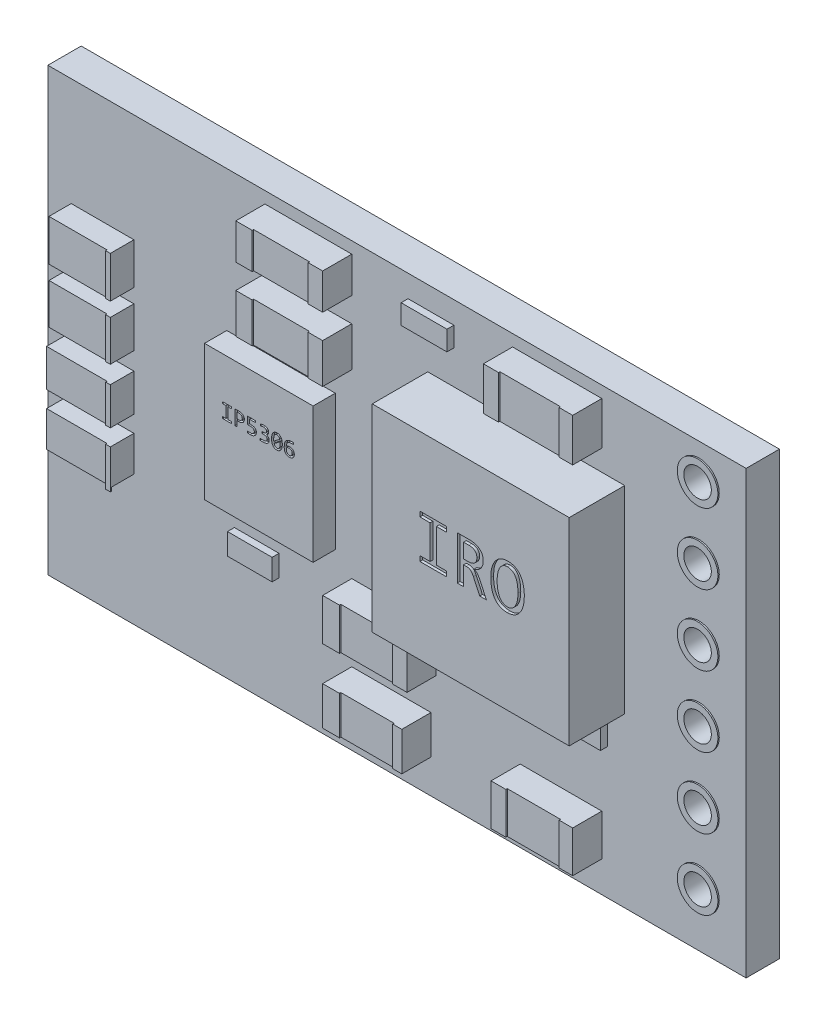
SolidWorks part; units mm, degrees
ref_plane "Plan de face" through (0, 0, 0) normal (0, 0, 1) x (1, 0, 0)
ref_plane "Plan de dessus" through (0, 0, 0) normal (0, 1, 0) x (1, 0, 0)
ref_plane "Plan de droite" through (0, 0, 0) normal (1, 0, 0) x (0, 0, -1)
sketch "Esquisse3" plane through (0, 0, 0) normal (0, 0, 1) x (1, 0, 0)
  line L0 (630.2148, 278.395) -> (630.1921, 275.8551) construction
  line L2 (606.726, 282.2036) -> (631.8802, 282.2036)
  line L3 (606.726, 282.2036) -> (606.726, 266.303)
  line L4 (606.726, 266.303) -> (631.8802, 266.303)
  line L5 (631.8802, 282.2036) -> (631.8802, 266.303)
  dimension "D1" = 2.54
sketch "condo" plane through (0, 0, 0) normal (0, 0, 1) x (1, 0, 0)
  line L1 (620.4109, 279.4811) -> (627.5068, 279.4811)
  line L2 (620.4109, 279.4811) -> (620.4109, 272.3562)
  line L3 (620.4109, 272.3562) -> (627.5068, 272.3562)
  line L4 (627.5068, 279.4811) -> (627.5068, 272.3562)
sketch "resistors" plane through (0, 0, 0) normal (0, 0, 1) x (1, 0, 0)
  line L1 (614.546, 281.7836) -> (617.6739, 281.7836)
  line L2 (614.546, 281.7836) -> (614.546, 280.4948)
  line L3 (614.546, 280.4948) -> (617.6739, 280.4948)
  line L4 (617.6739, 281.7836) -> (617.6739, 280.4948)
  line L5 (614.546, 279.6114) -> (617.6739, 279.6114)
  line L6 (614.546, 279.6114) -> (614.546, 278.1778)
  line L7 (614.546, 278.1778) -> (617.6739, 278.1778)
  line L8 (617.6739, 279.6114) -> (617.6739, 278.1778)
  line L9 (623.4665, 281.7836) -> (626.6814, 281.7836)
  line L10 (623.4665, 281.7836) -> (623.4665, 280.2341)
  line L11 (623.4665, 280.2341) -> (626.6814, 280.2341)
  line L12 (626.6814, 281.7836) -> (626.6814, 280.2341)
  line L13 (617.6739, 271.6611) -> (620.715, 271.6611)
  line L14 (617.6739, 271.6611) -> (617.6739, 270.1551)
  line L15 (617.6739, 270.1551) -> (620.715, 270.1551)
  line L16 (620.715, 271.6611) -> (620.715, 270.1551)
  line L17 (617.6739, 268.9097) -> (620.5268, 268.9097)
  line L18 (617.6739, 268.9097) -> (617.6739, 267.5195)
  line L19 (617.6739, 267.5195) -> (620.5268, 267.5195)
  line L20 (620.5268, 268.9097) -> (620.5268, 267.5195)
  line L21 (623.7416, 268.9097) -> (626.6814, 268.9097)
  line L22 (623.7416, 268.9097) -> (623.7416, 267.4181)
  line L23 (623.7416, 267.4181) -> (626.6814, 267.4181)
  line L24 (626.6814, 268.9097) -> (626.6814, 267.4181)
sketch "ic  et diodes" plane through (0, 0, 0) normal (0, 0, 1) x (1, 0, 0)
  line L1 (613.1702, 277.1496) -> (617.0802, 277.1496)
  line L2 (613.1702, 277.1496) -> (613.1702, 272.2694)
  line L3 (613.1702, 272.2694) -> (617.0802, 272.2694)
  line L4 (617.0802, 277.1496) -> (617.0802, 272.2694)
  line L5 (609.825, 278.3081) -> (607.5659, 278.3081)
  line L6 (609.825, 278.3081) -> (609.825, 276.8165)
  line L7 (609.825, 276.8165) -> (607.5659, 276.8165)
  line L8 (607.5659, 278.3081) -> (607.5659, 276.8165)
  line L9 (609.825, 276.3097) -> (607.5659, 276.3097)
  line L10 (609.825, 276.3097) -> (609.825, 274.847)
  line L11 (609.825, 274.847) -> (607.5659, 274.847)
  line L12 (607.5659, 276.3097) -> (607.5659, 274.847)
  line L13 (609.825, 274.2099) -> (607.479, 274.2099)
  line L14 (609.825, 274.2099) -> (609.825, 272.8631)
  line L15 (609.825, 272.8631) -> (607.479, 272.8631)
  line L16 (607.479, 274.2099) -> (607.479, 272.8631)
  line L17 (609.825, 272.2694) -> (607.479, 272.2694)
  line L18 (609.825, 272.2694) -> (609.825, 270.995)
  line L19 (609.825, 270.995) -> (607.479, 270.995)
  line L20 (607.479, 272.2694) -> (607.479, 270.995)
sketch "resistrors" plane through (0, 0, 0) normal (0, 0, 1) x (1, 0, 0)
  line L1 (619.7013, 281.4071) -> (621.3522, 281.4071)
  line L2 (619.7013, 281.4071) -> (619.7013, 280.6975)
  line L3 (619.7013, 280.6975) -> (621.3522, 280.6975)
  line L4 (621.3522, 281.4071) -> (621.3522, 280.6975)
  line L5 (613.4454, 271.1398) -> (615.0528, 271.1398)
  line L6 (613.4454, 271.1398) -> (613.4454, 270.3723)
  line L7 (613.4454, 270.3723) -> (615.0528, 270.3723)
  line L8 (615.0528, 271.1398) -> (615.0528, 270.3723)
  line L9 (622.5252, 271.8784) -> (624.0602, 271.8784)
  line L10 (622.5252, 271.8784) -> (622.5252, 271.1398)
  line L11 (622.5252, 271.1398) -> (624.0602, 271.1398)
  line L12 (624.0602, 271.8784) -> (624.0602, 271.1398)
  line L13 (625.2767, 271.8784) -> (626.8841, 271.8784)
  line L14 (625.2767, 271.8784) -> (625.2767, 271.024)
  line L15 (625.2767, 271.024) -> (626.8841, 271.024)
  line L16 (626.8841, 271.8784) -> (626.8841, 271.024)
sketch "pins" plane through (0, -0.1294, 0) normal (0, 0, 1) x (1, 0, 0)
  circle A0 centre (630.1816, 281.0754) radius 0.4958
  circle A1 centre (630.1816, 278.5354) radius 0.4958
  circle A2 centre (630.1816, 275.9954) radius 0.4958
  circle A3 centre (630.1816, 273.4554) radius 0.4958
  circle A4 centre (630.1816, 270.9154) radius 0.4958
  circle A5 centre (630.1816, 268.3754) radius 0.4958
  dimension "D1" = 6
extrude "Boss.-Extru.1" add sketch "Esquisse3" against normal blind 1.2
extrude "Boss.-Extru.2" add sketch "condo" along normal blind 2
extrude "Boss.-Extru.3" add sketch "ic  et diodes" along normal blind 0.8
extrude "Boss.-Extru.4" add sketch "resistrors" along normal blind 0.25
extrude "Boss.-Extru.5" add sketch "resistors" along normal blind 1
extrude "Enlèv. mat.-Extru.1" cut sketch "pins" against normal blind 11
sketch "Esquisse11" plane through (0, 0, 0.8) normal (0, 0, 1) x (1, 0, 0)
  text T0 "IP5306" font "Consolas" height in points 2
extrude "Enlèv. mat.-Extru.4" cut sketch "Esquisse11" against normal blind 0.1
sketch "Esquisse13" plane through (0, 0, 2) normal (0, 0, 1) x (1, 0, 0)
  text T0 "IRO" font "Consolas" height in points 6
extrude "Enlèv. mat.-Extru.5" cut sketch "Esquisse13" against normal blind 0.1
sketch "Esquisse14" plane through (0, 0, 0) normal (0, 0, 1) x (1, 0, 0)
  circle A0 centre (630.1816, 280.946) radius 0.4958
  circle A1 centre (630.1816, 280.946) radius 0.7316
  circle A2 centre (630.1816, 278.406) radius 0.7316
  circle A3 centre (630.1816, 278.406) radius 0.4958
  circle A4 centre (630.1816, 275.866) radius 0.7316
  circle A5 centre (630.1816, 275.866) radius 0.4958
  circle A6 centre (630.1816, 273.326) radius 0.7316
  circle A7 centre (630.1816, 273.326) radius 0.4958
  circle A8 centre (630.1816, 270.786) radius 0.7316
  circle A9 centre (630.1816, 270.786) radius 0.4958
  circle A10 centre (630.1816, 268.246) radius 0.7316
  circle A11 centre (630.1816, 268.246) radius 0.4958
  dimension "D1" = 6
extrude "Boss.-Extru.6" add sketch "Esquisse14" along normal blind 0.05
sketch "cathode diodes" plane through (0, 0, 0.8) normal (0, 0, 1) x (1, 0, 0)
  line L0 (609.825, 278.3081) -> (607.5659, 278.3081) construction
  line L1 (609.658, 278.3081) -> (609.825, 278.3081)
  line L2 (609.658, 278.3081) -> (609.658, 276.8165)
  line L3 (609.658, 276.8165) -> (609.825, 276.8165)
  line L4 (609.825, 278.3081) -> (609.825, 276.8165)
  line L5 (607.5659, 274.847) -> (609.825, 274.847) construction
  line L6 (609.825, 276.3097) -> (609.658, 276.3097)
  line L7 (609.825, 276.3097) -> (609.825, 274.847)
  line L8 (609.825, 274.847) -> (609.658, 274.847)
  line L9 (609.658, 276.3097) -> (609.658, 274.847)
  line L10 (607.479, 272.8631) -> (609.825, 272.8631) construction
  line L11 (609.825, 274.2099) -> (609.658, 274.2099)
  line L12 (609.825, 274.2099) -> (609.825, 272.8631)
  line L13 (609.825, 272.8631) -> (609.658, 272.8631)
  line L14 (609.658, 274.2099) -> (609.658, 272.8631)
  line L16 (609.825, 272.2694) -> (609.658, 272.2694)
  line L17 (609.825, 272.2694) -> (609.825, 270.8665)
  line L18 (609.825, 270.8665) -> (609.658, 270.8665)
  line L19 (609.658, 272.2694) -> (609.658, 270.8665)
extrude "Boss.-Extru.7" add sketch "cathode diodes" along normal blind 0.05
sketch "soudurecapa" plane through (0, 0, 1) normal (0, 0, 1) x (1, 0, 0)
  line L0 (614.546, 280.4948) -> (617.6739, 280.4948) construction
  line L1 (614.546, 281.7836) -> (615.1381, 281.7836)
  line L2 (614.546, 281.7836) -> (614.546, 280.4948)
  line L3 (614.546, 280.4948) -> (615.1381, 280.4948)
  line L4 (615.1381, 281.7836) -> (615.1381, 280.4948)
  line L5 (614.546, 280.4948) -> (617.6739, 280.4948) construction
  line L6 (617.6739, 281.7836) -> (617.1473, 281.7836)
  line L7 (617.6739, 281.7836) -> (617.6739, 280.4948)
  line L8 (617.6739, 280.4948) -> (617.1473, 280.4948)
  line L9 (617.1473, 281.7836) -> (617.1473, 280.4948)
  line L10 (614.546, 278.1778) -> (617.6739, 278.1778) construction
  line L11 (617.6739, 279.6114) -> (617.1473, 279.6114)
  line L12 (617.6739, 279.6114) -> (617.6739, 278.1778)
  line L13 (617.6739, 278.1778) -> (617.1473, 278.1778)
  line L14 (617.1473, 279.6114) -> (617.1473, 278.1778)
  line L15 (617.6739, 270.1551) -> (620.715, 270.1551) construction
  line L16 (614.546, 279.6114) -> (615.1381, 279.6114)
  line L17 (614.546, 279.6114) -> (614.546, 278.1778)
  line L18 (614.546, 278.1778) -> (615.1381, 278.1778)
  line L19 (615.1381, 279.6114) -> (615.1381, 278.1778)
  line L20 (617.6739, 271.6611) -> (618.2816, 271.6611)
  line L21 (617.6739, 271.6611) -> (617.6739, 270.1551)
  line L22 (617.6739, 270.1551) -> (618.2816, 270.1551)
  line L23 (618.2816, 271.6611) -> (618.2816, 270.1551)
  line L24 (617.6739, 270.1551) -> (620.715, 270.1551) construction
  line L25 (620.715, 271.6611) -> (620.1935, 271.6611)
  line L26 (620.715, 271.6611) -> (620.715, 270.1551)
  line L27 (620.715, 270.1551) -> (620.1935, 270.1551)
  line L28 (620.1935, 271.6611) -> (620.1935, 270.1551)
  line L29 (617.6739, 267.5195) -> (620.5268, 267.5195) construction
  line L30 (620.5268, 268.9097) -> (620.1935, 268.9097)
  line L31 (620.5268, 268.9097) -> (620.5268, 267.5195)
  line L32 (620.5268, 267.5195) -> (620.1935, 267.5195)
  line L33 (620.1935, 268.9097) -> (620.1935, 267.5195)
  line L34 (623.7416, 267.4181) -> (626.6814, 267.4181) construction
  line L35 (617.6739, 268.9097) -> (618.2816, 268.9097)
  line L36 (617.6739, 268.9097) -> (617.6739, 267.5195)
  line L37 (617.6739, 267.5195) -> (618.2816, 267.5195)
  line L38 (618.2816, 268.9097) -> (618.2816, 267.5195)
  line L39 (623.7416, 268.9097) -> (624.2767, 268.9097)
  line L40 (623.7416, 268.9097) -> (623.7416, 267.4181)
  line L41 (623.7416, 267.4181) -> (624.2767, 267.4181)
  line L42 (624.2767, 268.9097) -> (624.2767, 267.4181)
  line L43 (623.4665, 280.2341) -> (626.6814, 280.2341) construction
  line L44 (626.6814, 268.9097) -> (626.1887, 268.9097)
  line L45 (626.6814, 268.9097) -> (626.6814, 267.4181)
  line L46 (626.6814, 267.4181) -> (626.1887, 267.4181)
  line L47 (626.1887, 268.9097) -> (626.1887, 267.4181)
  line L48 (626.6814, 281.7836) -> (626.1887, 281.7836)
  line L49 (626.6814, 281.7836) -> (626.6814, 280.2341)
  line L50 (626.6814, 280.2341) -> (626.1887, 280.2341)
  line L51 (626.1887, 281.7836) -> (626.1887, 280.2341)
  line L52 (623.4665, 280.2341) -> (626.6814, 280.2341) construction
  line L53 (623.4665, 281.7836) -> (624.0092, 281.7836)
  line L54 (623.4665, 281.7836) -> (623.4665, 280.2341)
  line L55 (623.4665, 280.2341) -> (624.0092, 280.2341)
  line L56 (624.0092, 281.7836) -> (624.0092, 280.2341)
extrude "Boss.-Extru.8" add sketch "soudurecapa" along normal blind 0.05
sketch "Esquisse15" plane through (0, 0, 0) normal (0, 0, 1) x (1, 0, 0)
  line L0 (606.726, 274.2533) -> (634.3219, 274.2533) construction
  line L1 (606.726, 282.2036) -> (606.726, 266.303) construction
